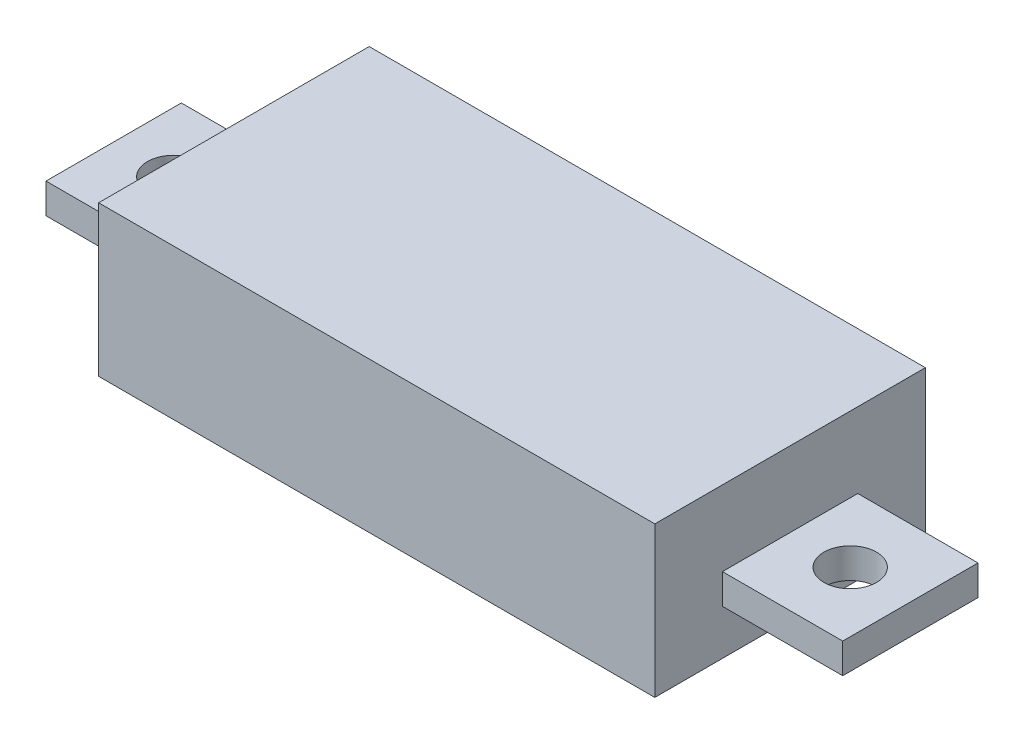
SolidWorks part; units mm, degrees
ref_plane "前视基准面" through (0, 0, 0) normal (0, 0, 1) x (1, 0, 0)
ref_plane "上视基准面" through (0, 0, 0) normal (0, 1, 0) x (1, 0, 0)
ref_plane "右视基准面" through (0, 0, 0) normal (1, 0, 0) x (0, 0, -1)
sketch "草图1" plane through (0, 0, 0) normal (0, 1, 0) x (1, 0, 0)
  line L1 (-45.7663, 28.3751) -> (-8.7663, 28.3751)
  line L2 (-45.7663, 28.3751) -> (-45.7663, 10.3751)
  line L3 (-45.7663, 10.3751) -> (-8.7663, 10.3751)
  line L4 (-8.7663, 28.3751) -> (-8.7663, 10.3751)
  dimension "D1" = 37
  dimension "D2" = 18
extrude "凸台-拉伸1" add sketch "草图1" along normal blind 10
sketch "草图2" plane through (-45.7663, 0, 0) normal (-1, 0, 0) x (0, 0, 1)
  line L0 (-28.3751, 10) -> (-10.3751, 10) construction
  line L1 (-14.8751, 5) -> (-23.8751, 5)
  line L2 (-14.8751, 5) -> (-14.8751, 3)
  line L3 (-14.8751, 3) -> (-23.8751, 3)
  line L4 (-23.8751, 5) -> (-23.8751, 3)
  point P6 (-19.3751, 5)
  point P7 (-19.3751, 10)
  dimension "D1" = 9
  dimension "D2" = 2
  dimension "D3" = 5
  dimension "D4" = 0
extrude "凸台-拉伸2" add sketch "草图2" along normal blind 8 and the other way blind 45
sketch "草图3" plane through (0, 5, 0) normal (0, 1, 0) x (1, 0, 0)
  line L0 (-45.7663, 23.8751) -> (-53.7663, 23.8751) construction
  line L1 (-0.7663, 23.8751) -> (-8.7663, 23.8751) construction
  line L2 (-0.7663, 14.8751) -> (-0.7663, 23.8751) construction
  line L3 (-53.7663, 14.8751) -> (-53.7663, 23.8751) construction
  circle A0 centre (-49.7663, 19.3751) radius 1.75
  circle A1 centre (-4.7663, 19.3751) radius 1.75
  point P8 (-4.7663, 23.8751)
  dimension "D1" = 3.5
  dimension "D2" = 3.5
  dimension "D3" = 4.5
  dimension "D4" = 4.5
  dimension "D5" = 4
  dimension "D6" = 4
extrude "切除-拉伸1" cut sketch "草图3" against normal blind 8
